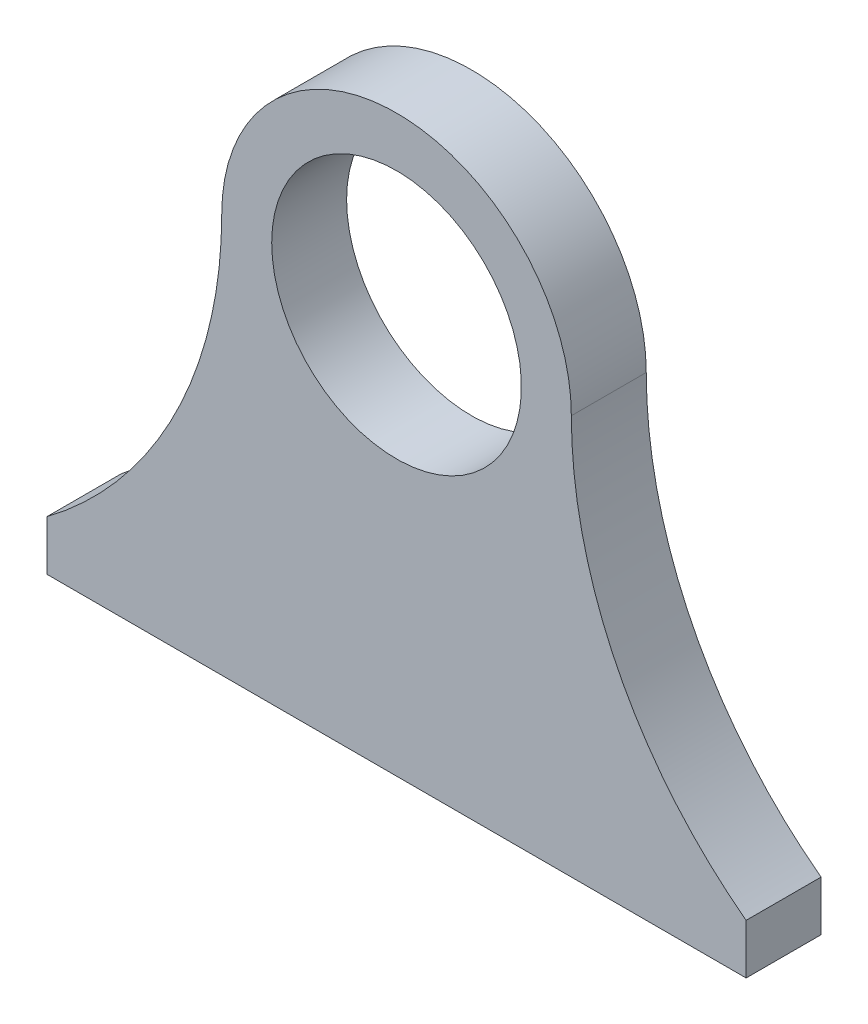
SolidWorks part; units mm, degrees
ref_plane "Front Plane" through (0, 0, 0) normal (0, 0, 1) x (1, 0, 0)
ref_plane "Top Plane" through (0, 0, 0) normal (0, 1, 0) x (1, 0, 0)
ref_plane "Right Plane" through (0, 0, 0) normal (1, 0, 0) x (0, 0, -1)
sketch "Sketch1" plane through (0, 0, 0) normal (0, 0, 1) x (1, 0, 0)
  line L2 (-22.225, -25.4) -> (22.225, -25.4)
  line L3 (0, 0) -> (0, -25.4) construction
  line L4 (-22.225, -22.225) -> (-22.225, -25.4)
  line L5 (22.225, -22.225) -> (22.225, -25.4)
  circle A0 centre (0, 0) radius 7.9375
  arc A1 (11.1125, 0) -> (-11.1125, 0) centre (0, 0) ccw
  circle A2 centre (0, 0) radius 11.1125 construction
  arc A3 (-11.1125, 0) -> (-22.225, -22.225) centre (-38.8938, 0) cw
  arc A4 (11.1125, 0) -> (22.225, -22.225) centre (38.8938, 0) ccw
  dimension "D1" = 15.875
  dimension "D3" = 25.4
  dimension "D4" = 44.45
  dimension "D5" = 3.175
  dimension "D6" = 3.175
  dimension "D2" = 3.175
extrude "Boss-Extrude1" add sketch "Sketch1" along normal blind 4.7625 contours A4 A1 A3 L4 L2 L5 A0
